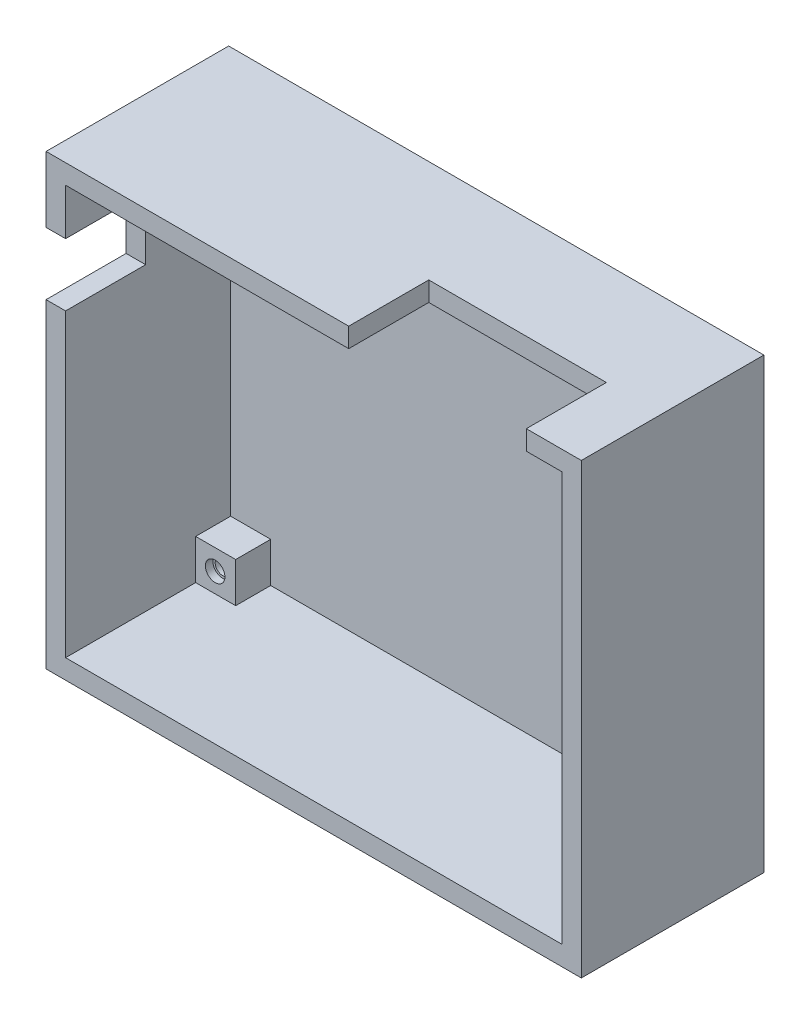
SolidWorks part; units mm, degrees
ref_plane "Plano frontal" through (0, 0, 0) normal (0, 0, 1) x (1, 0, 0)
ref_plane "Plano superior" through (0, 0, 0) normal (0, 1, 0) x (1, 0, 0)
ref_plane "Plano direito" through (0, 0, 0) normal (1, 0, 0) x (0, 0, -1)
sketch "Esboço1" plane through (0, 0, 0) normal (0, 0, 1) x (1, 0, 0)
  line L0 (0, 0) -> (107, 0)
  line L1 (107, -89.6) -> (0, -89.6)
  line L2 (107, 0) -> (107, -89.6)
  line L3 (0, -89.6) -> (0, 0)
extrude "Ressalto-extrusão2" add sketch "Esboço1" along normal blind 36.5
sketch "Esboço3" plane through (0, 0, 36.5) normal (0, 0, 1) x (1, 0, 0)
  line L0 (0, 0) -> (3.9, 0)
  line L1 (107, 0) -> (0, 0) construction
  line L2 (3.9, 0) -> (3.9, -3.9)
  line L4 (7.8, -6.3) -> (7.8, -7.8)
  line L6 (3.9, -11.9) -> (11.9, -11.9)
  line L7 (11.9, -11.9) -> (11.9, -7.8)
  line L8 (7.8, -7.8) -> (9.3, -7.8)
  line L10 (95.1, -81.8) -> (11.9, -81.8)
  line L12 (11.9, -7.8) -> (95.1, -7.8)
  line L13 (99.2, -11.9) -> (103.1, -11.9)
  line L14 (99.2, -77.7) -> (95.1, -77.7)
  line L15 (7.8, -77.7) -> (3.9, -77.7)
  line L16 (3.9, -77.7) -> (3.9, -11.9)
  line L17 (99.2, -11.9) -> (95.1, -11.9)
  line L18 (99.2, -77.7) -> (103.1, -77.7)
  line L19 (103.1, -77.7) -> (103.1, -11.9)
  line L20 (95.1, -11.9) -> (95.1, -7.8)
  line L21 (7.8, -77.7) -> (11.9, -77.7)
  line L22 (11.9, -77.7) -> (11.9, -81.8)
  line L23 (95.1, -77.7) -> (95.1, -81.8)
  circle A0 centre (7.8, -7.8) radius 1.5
  dimension "D1" = 3
extrude "Corte-extrusão2" cut sketch "Esboço3" against normal blind 33 contours L23 L14 L18 L19 L13 L17 L20 L12 L7 L6 L16 L15 L21 L22 L10
sketch "Esboço4" plane through (0, 0, 36.5) normal (0, 0, 1) x (1, 0, 0)
  line L0 (3.9, -11.9) -> (3.9, -3.9)
  line L1 (3.9, -3.9) -> (11.9, -3.9)
  line L2 (11.9, -3.9) -> (11.9, -7.8)
  line L3 (11.9, -7.8) -> (11.9, -11.9)
  line L4 (11.9, -11.9) -> (3.9, -11.9)
  line L5 (103.1, -11.9) -> (103.1, -3.9)
  line L6 (103.1, -3.9) -> (95.1, -3.9)
  line L7 (95.1, -3.9) -> (95.1, -7.8)
  line L8 (95.1, -7.8) -> (95.1, -11.9)
  line L9 (95.1, -11.9) -> (103.1, -11.9)
  line L10 (3.9, -77.7) -> (3.9, -85.7)
  line L11 (3.9, -85.7) -> (11.9, -85.7)
  line L12 (11.9, -85.7) -> (11.9, -77.7)
  line L13 (11.9, -77.7) -> (11.9, -81.8) construction
  line L14 (11.9, -77.7) -> (11.9, -81.8) construction
  line L15 (11.9, -77.7) -> (3.9, -77.7)
  line L16 (103.1, -77.7) -> (103.1, -85.7)
  line L17 (103.1, -85.7) -> (95.1, -85.7)
  line L18 (95.1, -85.7) -> (95.1, -77.7)
  line L19 (95.1, -77.7) -> (103.1, -77.7)
extrude "Corte-extrusão3" cut sketch "Esboço4" against normal blind 26
sketch "Esboço5" plane through (0, 0, 36.5) normal (0, 0, 1) x (1, 0, 0)
  line L0 (11.9, -3.9) -> (95.1, -3.9)
  line L1 (95.1, -3.9) -> (95.1, -7.8)
  line L2 (95.1, -7.8) -> (11.9, -7.8)
  line L3 (11.9, -7.8) -> (11.9, -3.9)
  line L4 (11.9, -77.7) -> (95.1, -77.7)
  line L5 (95.1, -77.7) -> (95.1, -81.8)
  line L6 (95.1, -81.8) -> (11.9, -81.8)
  line L7 (11.9, -81.8) -> (11.9, -77.7)
extrude "Corte-extrusão4" cut sketch "Esboço5" against normal blind 33
sketch "Esboço6" plane through (0, 0, 36.5) normal (0, 0, 1) x (1, 0, 0)
  line L0 (11.9, -85.7) -> (95.1, -85.7)
  line L1 (95.1, -85.7) -> (95.1, -81.8)
  line L2 (95.1, -81.8) -> (11.9, -81.8)
  line L3 (11.9, -81.8) -> (11.9, -85.7)
extrude "Corte-extrusão5" cut sketch "Esboço6" against normal blind 33
sketch "Esboço7" plane through (0, 0, 36.5) normal (0, 0, 1) x (1, 0, 0)
  line L0 (103.1, -3.9) -> (96, -3.9)
  line L1 (103.1, -3.9) -> (3.9, -3.9) construction
  line L2 (96, -3.9) -> (96, 0)
  line L3 (107, 0) -> (0, 0) construction
  line L4 (96, 0) -> (60.5, 0)
  line L5 (60.5, 0) -> (60.5, -3.9)
  line L6 (60.5, -3.9) -> (96, -3.9)
  line M4 (107, 0) -> (0, 0)
  line M8 (3.9, -3.9) -> (103.1, -3.9)
extrude "Corte-extrusão6" cut sketch "Esboço7" against normal blind 16 contours L5 L2 M4 M8
sketch "Esboço9" plane through (0, 0, 36.5) normal (0, 0, 1) x (1, 0, 0)
  line L0 (3.9, -3.9) -> (3.9, -13.16)
  line L1 (3.9, -77.7) -> (3.9, -11.9) construction
  line L2 (3.9, -13.16) -> (0, -13.16)
  line L3 (0, 0) -> (0, -89.6) construction
  line L4 (3.9, -85.7) -> (3.9, -25.66)
  line L5 (3.9, -25.66) -> (0, -25.66)
  line L6 (0, -25.66) -> (0, -13.16)
  line L7 (3.9, -13.16) -> (3.9, -25.66)
  line L8 (0, -25.66) -> (0, -13.16)
  line M8 (3.9, -85.7) -> (3.9, -3.9)
  line M12 (0, 0) -> (0, -89.6)
extrude "Corte-extrusão7" cut sketch "Esboço9" against normal blind 16 contours L5 L2 M8 M12
sketch "Esboço10" plane through (0, 0, 10.5) normal (0, 0, 1) x (1, 0, 0)
  line L0 (3.9, -3.9) -> (3.9, -7.8)
  line L1 (3.9, -3.9) -> (3.9, -11.9) construction
  circle A0 centre (7.8, -7.8) radius 1.95
  dimension "D1" = 3.9
extrude "Corte-extrusão8" cut sketch "Esboço10" against normal blind 1.5 contours A0
sketch "Esboço11" plane through (0, 0, 10.5) normal (0, 0, 1) x (1, 0, 0)
  line L0 (103.1, -3.9) -> (103.1, -7.8)
  line L1 (103.1, -11.9) -> (103.1, -3.9) construction
  circle A0 centre (99.2, -7.8) radius 1.95
  dimension "D1" = 3.9
extrude "Corte-extrusão9" cut sketch "Esboço11" against normal blind 1.5 contours A0
sketch "Esboço12" plane through (0, 0, 10.5) normal (0, 0, 1) x (1, 0, 0)
  line L0 (103.1, -85.7) -> (99.2, -85.7)
  line L1 (95.1, -85.7) -> (103.1, -85.7) construction
  line L2 (99.2, -85.7) -> (99.2, -81.8)
  circle A0 centre (99.2, -81.8) radius 1.95
  dimension "D1" = 3.9
extrude "Corte-extrusão10" cut sketch "Esboço12" against normal blind 1.5
sketch "Esboço13" plane through (0, 0, 10.5) normal (0, 0, 1) x (1, 0, 0)
  line L0 (3.9, -85.7) -> (7.8, -85.7)
  line L1 (3.9, -85.7) -> (11.9, -85.7) construction
  line L2 (7.8, -85.7) -> (7.8, -81.8)
  circle A0 centre (7.8, -81.8) radius 1.95
  dimension "D1" = 3.9
extrude "Corte-extrusão11" cut sketch "Esboço13" against normal blind 1.5
sketch "Esboço14" plane through (0, 0, 9) normal (0, 0, 1) x (1, 0, 0)
  circle A0 centre (7.8, -7.8) radius 1.5
  dimension "D1" = 3
extrude "Corte-extrusão12" cut sketch "Esboço14" against normal blind 7 contours A0
sketch "Esboço15" plane through (0, 0, 9) normal (0, 0, 1) x (1, 0, 0)
  circle A0 centre (99.2, -7.8) radius 1.5
  dimension "D1" = 3
extrude "Corte-extrusão13" cut sketch "Esboço15" against normal blind 7 contours A0
sketch "Esboço16" plane through (0, 0, 9) normal (0, 0, 1) x (1, 0, 0)
  circle A0 centre (99.2, -81.8) radius 1.5
  dimension "D1" = 3
extrude "Corte-extrusão14" cut sketch "Esboço16" against normal blind 7 contours A0
sketch "Esboço17" plane through (0, 0, 9) normal (0, 0, 1) x (1, 0, 0)
  circle A0 centre (7.8, -81.8) radius 1.5
  dimension "D1" = 3
extrude "Corte-extrusão15" cut sketch "Esboço17" against normal blind 7 contours A0
